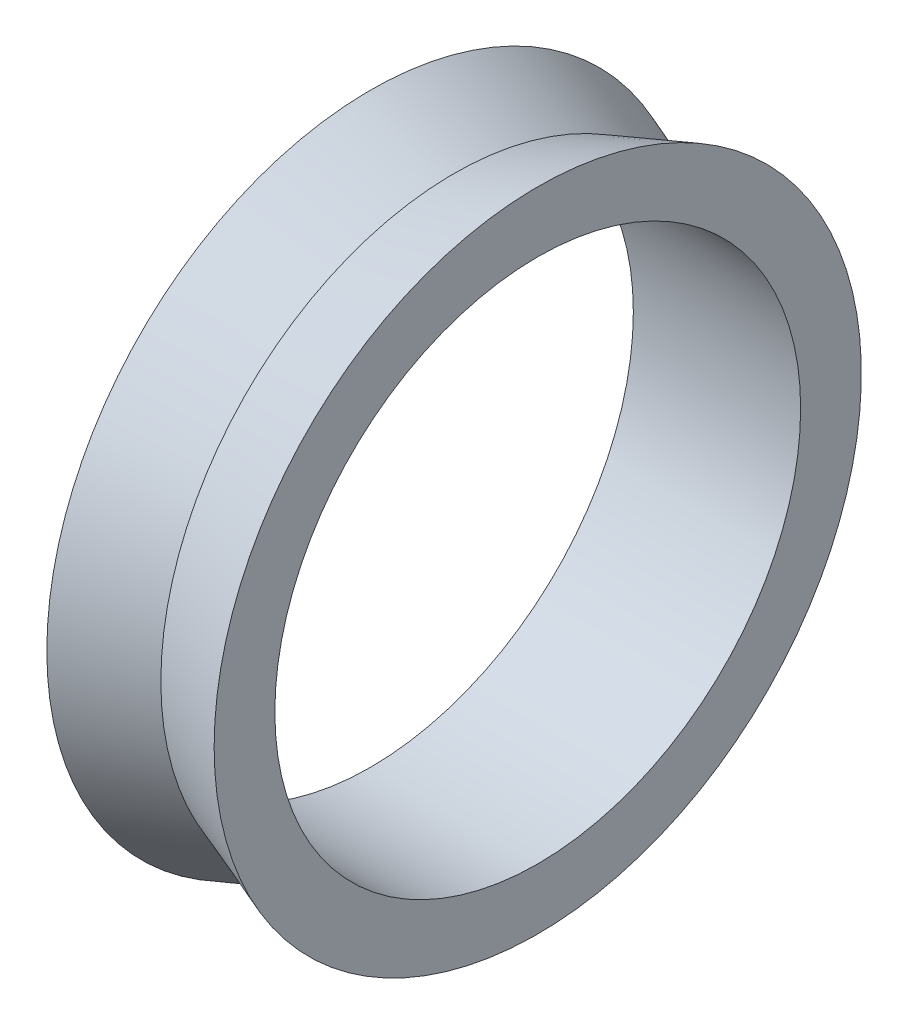
SolidWorks part; units mm, degrees
ref_plane "Front Plane" through (0, 0, 0) normal (0, 0, 1) x (1, 0, 0)
ref_plane "Top Plane" through (0, 0, 0) normal (0, 1, 0) x (1, 0, 0)
ref_plane "Right Plane" through (0, 0, 0) normal (1, 0, 0) x (0, 0, -1)
sketch "Sketch1" plane through (0, 0, 0) normal (0, 0, 1) x (1, 0, 0)
  line L0 (-3.5, 11) -> (3.5, 11)
  line L1 (0, 11) -> (0, 0) construction
  line L2 (-3.5, 11) -> (-3.5, 13.54)
  line L3 (-3.5, 13.54) -> (0, 12.27)
  line L4 (3.5, 13.54) -> (0, 12.27)
  line L5 (3.5, 11) -> (3.5, 13.54)
  line L6 (0, 0) -> (9.4357, 0)
  line L7 (55, 0) -> (-55, 0) construction
  dimension "D1" = 7
  dimension "D2" = 11
  dimension "D3" = 2.54
  dimension "D4" = 1.27
revolve "Revolve1" add sketch "Sketch1" angle 360 about L6
